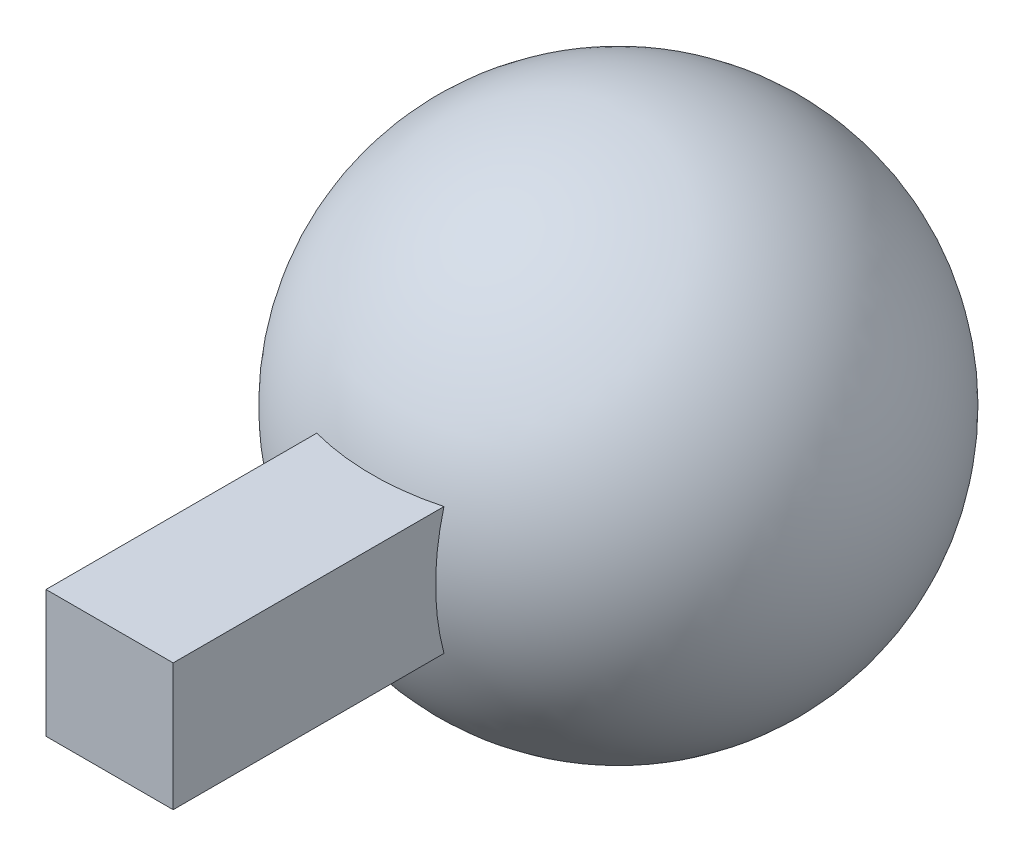
SolidWorks part; units mm, degrees
ref_plane "Plan de face" through (0, 0, 0) normal (0, 0, 1) x (1, 0, 0)
ref_plane "Plan de dessus" through (0, 0, 0) normal (0, 1, 0) x (1, 0, 0)
ref_plane "Plan de droite" through (0, 0, 0) normal (1, 0, 0) x (0, 0, -1)
sketch "Esquisse1" plane through (0, 0, 0) normal (0, 0, 1) x (1, 0, 0)
  line L0 (0, 4) -> (0, -4)
  arc A0 (0, -4) -> (0, 4) centre (0, 0) cw
  dimension "D1" = 4
revolve "Révolution1" add sketch "Esquisse1" angle 360 about L0
sketch "Esquisse2" plane through (0, 0, 0) normal (0, 0, 1) x (1, 0, 0)
  line L1 (-1, 1) -> (1, 1)
  line L2 (-1, 1) -> (-1, -1)
  line L3 (-1, -1) -> (1, -1)
  line L4 (1, 1) -> (1, -1)
  dimension "D1" = 2
  dimension "D2" = 2
  dimension "D3" = 1
  dimension "D4" = 1
extrude "Boss.-Extru.1" add sketch "Esquisse2" along normal blind 8
